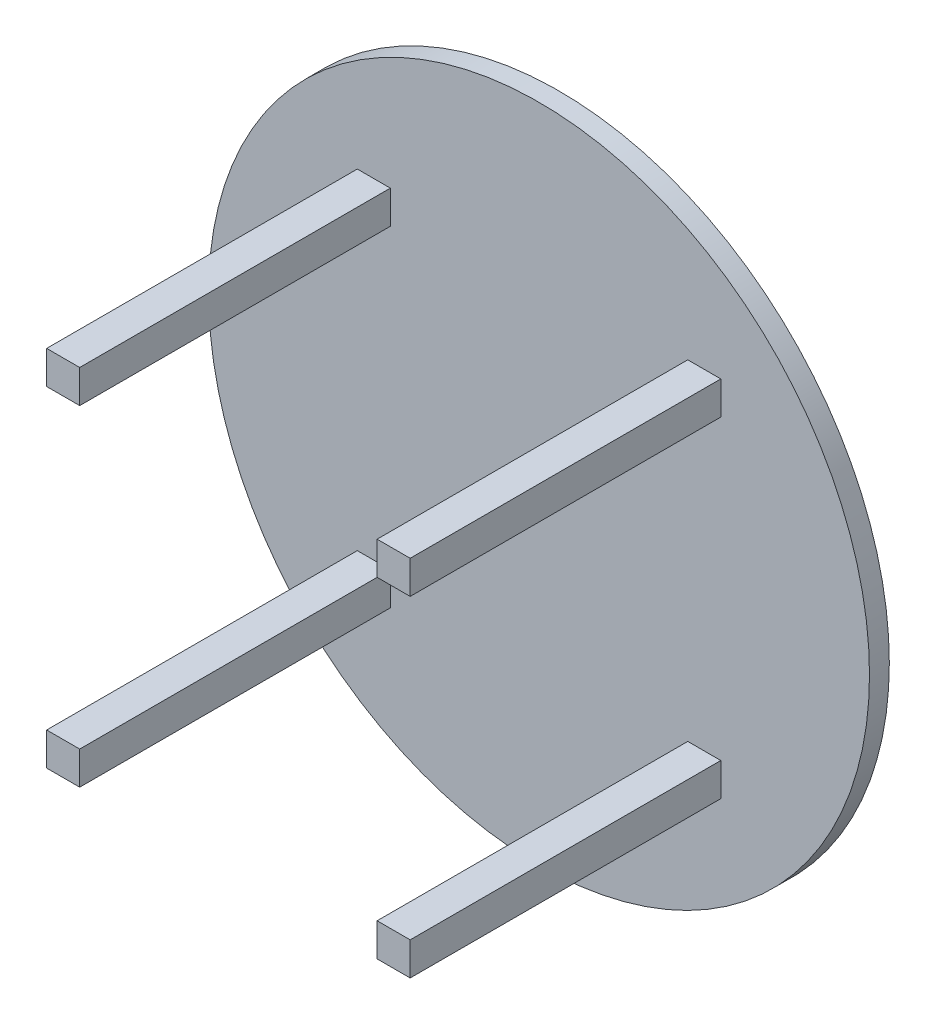
SolidWorks part; units mm, degrees
ref_plane "前视基准面" through (0, 0, 0) normal (0, 0, 1) x (1, 0, 0)
ref_plane "上视基准面" through (0, 0, 0) normal (0, 1, 0) x (1, 0, 0)
ref_plane "右视基准面" through (0, 0, 0) normal (1, 0, 0) x (0, 0, -1)
other "Configuration Table"
sketch "草图1" plane through (0, 0, 0) normal (0, 0, 1) x (1, 0, 0)
  circle A0 centre (0, 0) radius 500
extrude "凸台-拉伸1" add sketch "草图1" along normal blind 30
sketch "草图2" plane through (0, 0, 0) normal (0, 0, 1) x (1, 0, 0)
  line L1 (225, 225) -> (275, 225)
  line L2 (225, 225) -> (225, 275)
  line L3 (225, 275) -> (275, 275)
  line L4 (275, 225) -> (275, 275)
  line L5 (225, 225) -> (275, 275) construction
  line L6 (225, 275) -> (275, 225) construction
  point P0 (250, 250)
extrude "凸台-拉伸2" add sketch "草图2" along normal blind 500
sketch "草图3" plane through (0, 0, 0) normal (0, 0, 1) x (1, 0, 0)
  line L1 (225, -275) -> (275, -275)
  line L2 (225, -275) -> (225, -225)
  line L3 (225, -225) -> (275, -225)
  line L4 (275, -275) -> (275, -225)
  line L5 (225, -275) -> (275, -225) construction
  line L6 (225, -225) -> (275, -275) construction
  point P0 (250, -250)
extrude "凸台-拉伸3" add sketch "草图3" along normal blind 500
sketch "草图4" plane through (0, 0, 0) normal (0, 0, 1) x (1, 0, 0)
  line L1 (-275, 225) -> (-225, 225)
  line L2 (-275, 225) -> (-275, 275)
  line L3 (-275, 275) -> (-225, 275)
  line L4 (-225, 225) -> (-225, 275)
  line L5 (-275, 225) -> (-225, 275) construction
  line L6 (-275, 275) -> (-225, 225) construction
  point P0 (-250, 250)
  point P5 (0, 0)
extrude "凸台-拉伸4" add sketch "草图4" along normal blind 500
sketch "草图5" plane through (0, 0, 0) normal (0, 0, 1) x (1, 0, 0)
  line L1 (-275, -275) -> (-225, -275)
  line L2 (-275, -275) -> (-275, -225)
  line L3 (-275, -225) -> (-225, -225)
  line L4 (-225, -275) -> (-225, -225)
  line L5 (-275, -275) -> (-225, -225) construction
  line L6 (-275, -225) -> (-225, -275) construction
  point P0 (-250, -250)
  point P5 (0, 0)
extrude "凸台-拉伸5" add sketch "草图5" along normal blind 500
